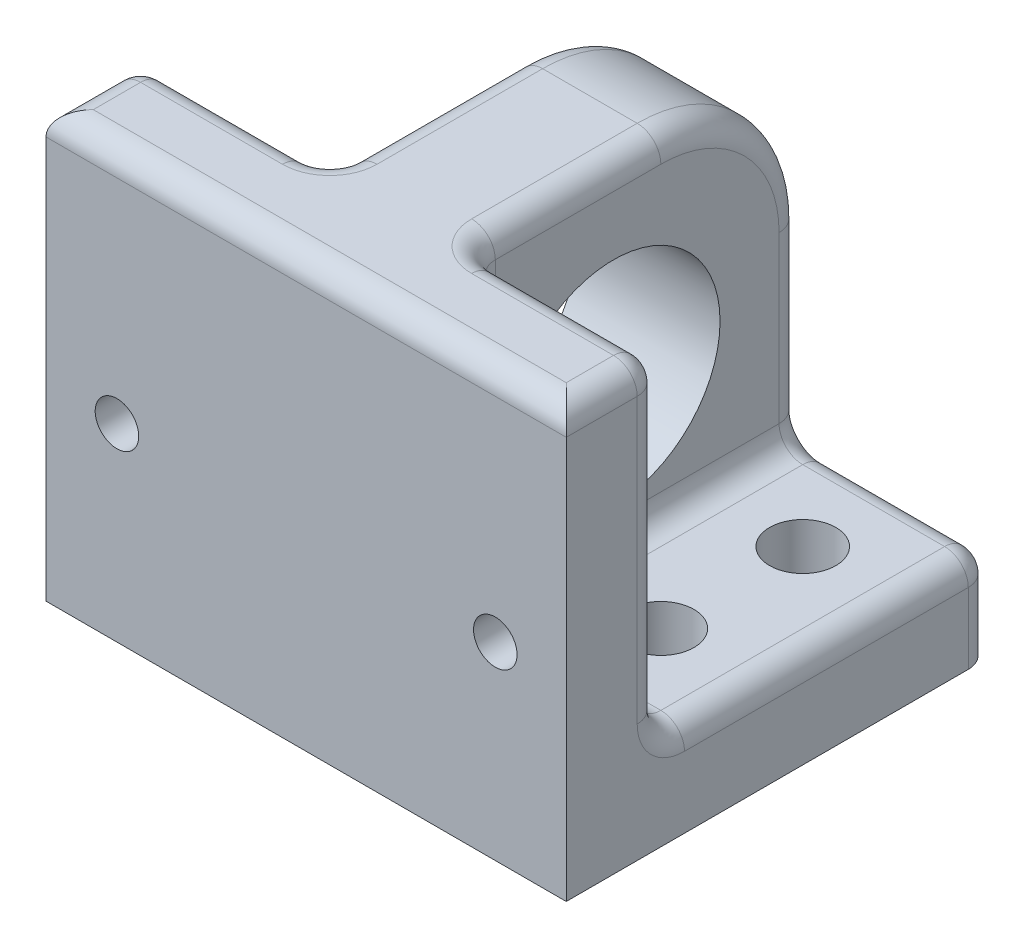
SolidWorks part; units mm, degrees
ref_plane "Front Plane" through (0, 0, 0) normal (0, 0, 1) x (1, 0, 0)
ref_plane "Top Plane" through (0, 0, 0) normal (0, 1, 0) x (1, 0, 0)
ref_plane "Right Plane" through (0, 0, 0) normal (1, 0, 0) x (0, 0, -1)
sketch "Sketch1" plane through (0, 0, 0) normal (1, 0, 0) x (0, 0, -1)
  line L1 (0, 0) -> (57.15, 0)
  line L2 (0, 0) -> (0, 57.15)
  line L3 (0, 57.15) -> (38.1, 57.15)
  line L4 (57.15, 0) -> (57.15, 38.1)
  circle A0 centre (31.75, 31.75) radius 14.3002
  arc A1 (57.15, 38.1) -> (38.1, 57.15) centre (38.1, 38.1) ccw
  dimension "D2" = 28.6004
  dimension "D6" = 19.05
  dimension "D1" = 57.15
  dimension "D3" = 57.15
  dimension "D4" = 31.75
  dimension "D5" = 31.75
extrude "Boss-Extrude1" add sketch "Sketch1" along normal blind 69.85
sketch "Sketch2" plane through (0, 57.15, 0) normal (0, 1, 0) x (1, 0, 0)
  line L0 (0, 38.1) -> (0, 0) construction
  line L1 (0, 12.7) -> (25.4, 12.7)
  line L2 (0, 12.7) -> (0, 57.15)
  line L3 (0, 57.15) -> (25.4, 57.15)
  line L4 (25.4, 12.7) -> (25.4, 57.15)
  line L5 (69.85, 57.15) -> (0, 57.15) construction
  line L11 (69.85, 0) -> (0, 0) construction
  line L12 (34.925, 57.15) -> (34.925, 0) construction
  line L13 (44.45, 12.7) -> (44.45, 57.15)
  line L14 (69.85, 57.15) -> (44.45, 57.15)
  line L15 (69.85, 12.7) -> (69.85, 57.15)
  line L16 (69.85, 12.7) -> (44.45, 12.7)
  dimension "D1" = 12.7
  dimension "D2" = 25.4
extrude "Cut-Extrude1" cut sketch "Sketch2" against normal blind 44.45
fillet "Fillet1" radius 3.175 25 edges at (12.7, 57.15, -12.7) (57.15, 57.15, -12.7) (25.4, 57.15, -25.4) (44.45, 57.15, -25.4) (25.4, 51.5704, -51.5704) (44.45, 51.5704, -51.5704) (0, 34.925, -12.7) (25.4, 25.4, -57.15) (69.85, 34.925, -12.7) (44.45, 25.4, -57.15) (0, 12.7, -34.925) (12.7, 12.7, -12.7) (25.4, 34.925, -12.7) (25.4, 12.7, -34.925) (12.7, 12.7, -57.15) (69.85, 12.7, -34.925) (57.15, 12.7, -57.15) (0, 6.35, -57.15) (69.85, 6.35, -57.15) (44.45, 12.7, -34.925) (57.15, 12.7, -12.7) (44.45, 34.925, -12.7) (0, 57.15, -6.35) (69.85, 57.15, -6.35) (34.925, 57.15, 0)
sketch "Sketch3" plane through (0, 0, 0) normal (0, 0, 1) x (1, 0, 0)
  line L1 (69.85, 0) -> (0, 0) construction
  line L2 (34.925, 53.975) -> (34.925, 0) construction
  line L3 (69.85, 53.975) -> (0, 53.975) construction
  circle A0 centre (9.525, 25.4) radius 2.921
  circle A2 centre (60.325, 25.4) radius 2.921
  dimension "D3" = 5.842
  dimension "D1" = 25.4
  dimension "D2" = 25.4
extrude "Cut-Extrude2" cut sketch "Sketch3" against normal through all
sketch "Sketch4" plane through (0, 0, 0) normal (0, -1, 0) x (1, 0, 0)
  line L0 (69.85, 0) -> (69.85, -53.975) construction
  line L1 (66.675, -57.15) -> (3.175, -57.15) construction
  line L2 (34.925, -57.15) -> (34.925, 0) construction
  line L3 (69.85, 0) -> (0, 0) construction
  circle A0 centre (57.15, -25.4) radius 2.921
  circle A1 centre (57.15, -44.45) radius 2.921
  circle A4 centre (12.7, -25.4) radius 2.921
  circle A5 centre (12.7, -44.45) radius 2.921
  dimension "D1" = 5.842
  dimension "D2" = 12.7
  dimension "D3" = 12.7
  dimension "D4" = 19.05
extrude "Cut-Extrude3" cut sketch "Sketch4" against normal through all
sketch "Sketch5" plane through (0, 12.7, 0) normal (0, 1, 0) x (1, 0, 0)
  circle A0 centre (12.7, 25.4) radius 4.445
  circle A1 centre (12.7, 44.45) radius 4.445
  circle A2 centre (57.15, 44.45) radius 4.445
  circle A3 centre (57.15, 25.4) radius 4.445
  dimension "D1" = 8.89
extrude "Cut-Extrude4" cut sketch "Sketch5" against normal blind 6.35
sketch "Sketch6" plane through (0, 0, -12.7) normal (0, 0, -1) x (-1, 0, 0)
  line L1 (-57.3921, 30.48) -> (-63.2579, 30.48)
  line L2 (-63.2579, 30.48) -> (-66.1909, 25.4)
  line L3 (-66.1909, 25.4) -> (-63.2579, 20.32)
  line L4 (-63.2579, 20.32) -> (-57.3921, 20.32)
  line L5 (-57.3921, 20.32) -> (-54.4591, 25.4)
  line L6 (-54.4591, 25.4) -> (-57.3921, 30.48)
  line L7 (-6.5921, 30.48) -> (-12.4579, 30.48)
  line L8 (-12.4579, 30.48) -> (-15.3909, 25.4)
  line L9 (-15.3909, 25.4) -> (-12.4579, 20.32)
  line L10 (-12.4579, 20.32) -> (-6.5921, 20.32)
  line L11 (-6.5921, 20.32) -> (-3.6591, 25.4)
  line L12 (-3.6591, 25.4) -> (-6.5921, 30.48)
  circle A0 centre (-60.325, 25.4) radius 5.08 construction
  circle A1 centre (-9.525, 25.4) radius 5.08 construction
  point P10 (-60.325, 30.48)
  dimension "D1" = 10.16
extrude "Cut-Extrude5" cut sketch "Sketch6" against normal blind 7.62
